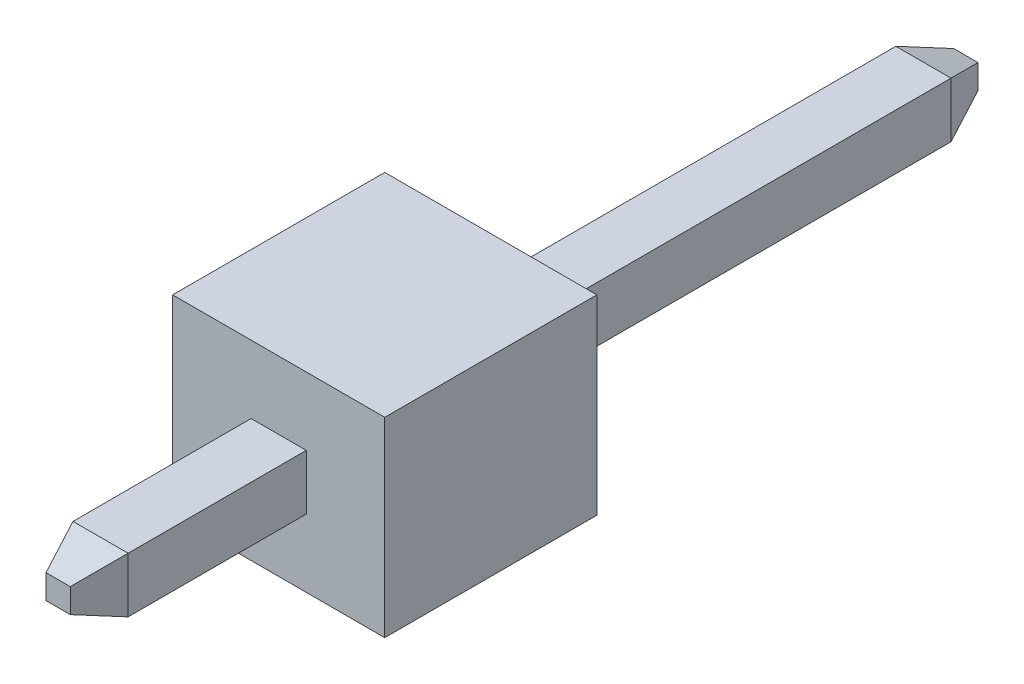
SolidWorks part; units mm, degrees
ref_plane "Front Plane" through (0, 0, 0) normal (0, 0, 1) x (1, 0, 0)
ref_plane "Top Plane" through (0, 0, 0) normal (0, 1, 0) x (1, 0, 0)
ref_plane "Right Plane" through (0, 0, 0) normal (1, 0, 0) x (0, 0, -1)
sketch "Sketch1" plane through (0, 0, 0) normal (0, 0, 1) x (1, 0, 0)
  line L1 (1.25, -1.125) -> (-1.25, -1.125)
  line L2 (1.25, -1.125) -> (1.25, 1.125)
  line L3 (1.25, 1.125) -> (-1.25, 1.125)
  line L4 (-1.25, -1.125) -> (-1.25, 1.125)
  line L5 (1.25, -1.125) -> (-1.25, 1.125) construction
  line L6 (1.25, 1.125) -> (-1.25, -1.125) construction
  point P0 (0, 0)
  dimension "D1" = 2.25
  dimension "D2" = 2.5
extrude "Boss-Extrude1" add sketch "Sketch1" along normal mid plane 2.5
sketch "Sketch2" plane through (0, 0, 0) normal (0, 0, 1) x (1, 0, 0)
  line L1 (0.325, -0.325) -> (-0.325, -0.325)
  line L2 (0.325, -0.325) -> (0.325, 0.325)
  line L3 (0.325, 0.325) -> (-0.325, 0.325)
  line L4 (-0.325, -0.325) -> (-0.325, 0.325)
  line L5 (0.325, -0.325) -> (-0.325, 0.325) construction
  line L6 (0.325, 0.325) -> (-0.325, -0.325) construction
  circle A0 centre (0, 0) radius 0.325 construction
  dimension "D1" = 0.65
extrude "Boss-Extrude2" add sketch "Sketch2" along normal blind 3.35 and the other way blind 6.35
sketch "Sketch3" plane through (0, 0, -6.35) normal (0, 0, -1) x (-1, 0, 0)
  line L1 (0.325, -0.325) -> (-0.325, -0.325)
  line L2 (0.325, -0.325) -> (0.325, 0.325)
  line L3 (0.325, 0.325) -> (-0.325, 0.325)
  line L4 (-0.325, -0.325) -> (-0.325, 0.325)
  line L5 (0.325, -0.325) -> (-0.325, 0.325) construction
  line L6 (0.325, 0.325) -> (-0.325, -0.325) construction
  point P0 (0, 0)
extrude "Boss-Extrude3" add sketch "Sketch3" along normal blind 0.5 draft 20
sketch "Sketch5" plane through (0, 0, 3.35) normal (0, 0, 1) x (1, 0, 0)
  line L0 (0.325, -0.325) -> (-0.325, 0.325) construction
  line L1 (-0.325, -0.325) -> (0.325, 0.325) construction
  line L2 (0.325, 0.325) -> (-0.325, 0.325) construction
  point P9 (0, 0)
sketch "Sketch7" plane through (0, 0, 3.35) normal (0, 0, 1) x (1, 0, 0)
  line L4 (-0.325, 0.325) -> (-0.325, -0.325)
  line L5 (-0.325, -0.325) -> (0.325, -0.325)
  line L6 (0.325, -0.325) -> (0.325, 0.325)
  line L7 (0.325, 0.325) -> (-0.325, 0.325)
  line L8 (-0.325, 0.325) -> (-0.325, -0.325)
  line L9 (-0.325, -0.325) -> (0.325, -0.325)
  line L10 (0.325, -0.325) -> (0.325, 0.325)
  line L11 (0.325, 0.325) -> (-0.325, 0.325)
  dimension "D1" = 0
extrude "Boss-Extrude6" add sketch "Sketch7" along normal blind 0.5 draft 20
